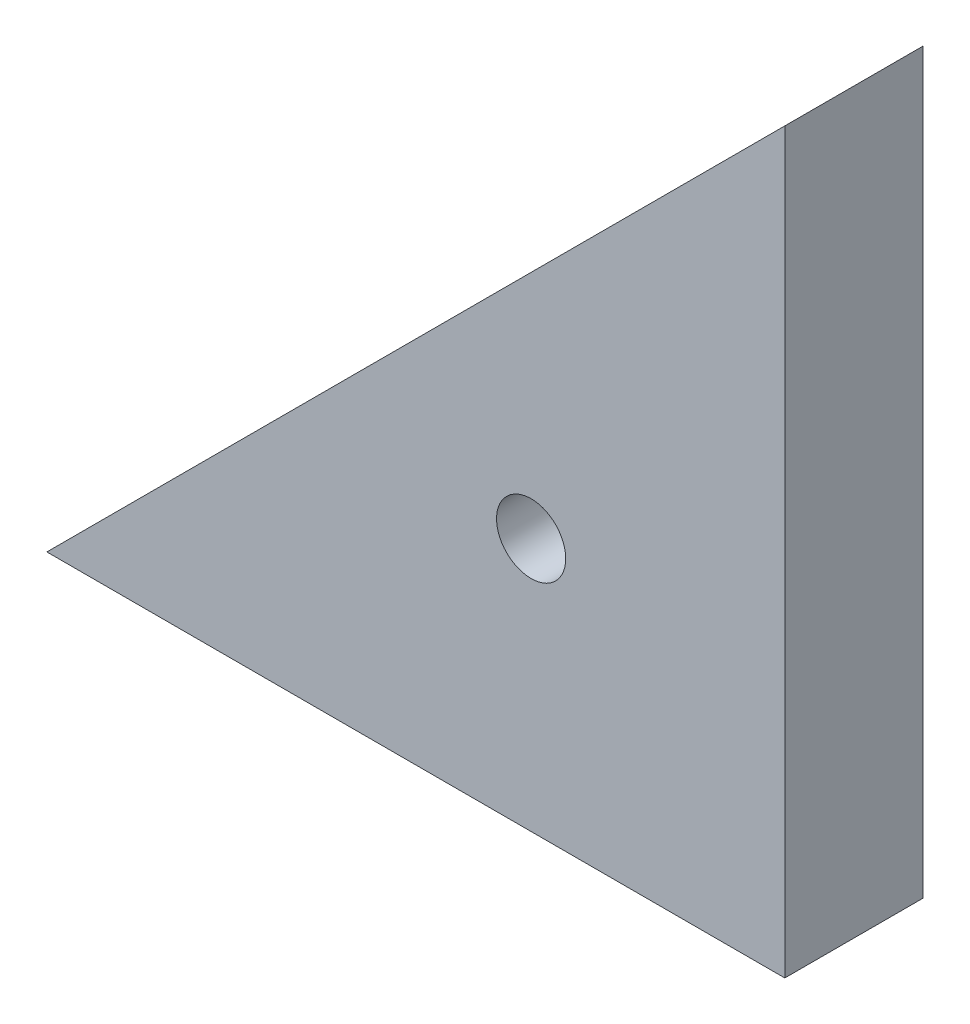
SolidWorks part; units mm, degrees
material "MDF"
ref_plane "Plano frontal" through (0, 0, 0) normal (0, 0, 1) x (1, 0, 0)
ref_plane "Plano superior" through (0, 0, 0) normal (0, 1, 0) x (1, 0, 0)
ref_plane "Plano direito" through (0, 0, 0) normal (1, 0, 0) x (0, 0, -1)
sketch "Esboço1" plane through (0, 0, 0) normal (0, 0, 1) x (1, 0, 0)
  line L0 (-16, 0) -> (16, 0)
  line L1 (16, 0) -> (16, 32)
  line L2 (16, 32) -> (-16, 0)
  line L3 (16, 0) -> (0, 16) construction
  circle A0 centre (5, 11) radius 1.5
  dimension "D3" = 11
  dimension "D4" = 3
  dimension "D1" = 16
  dimension "D2" = 16
extrude "Ressalto-extrusão1" add sketch "Esboço1" along normal blind 6
